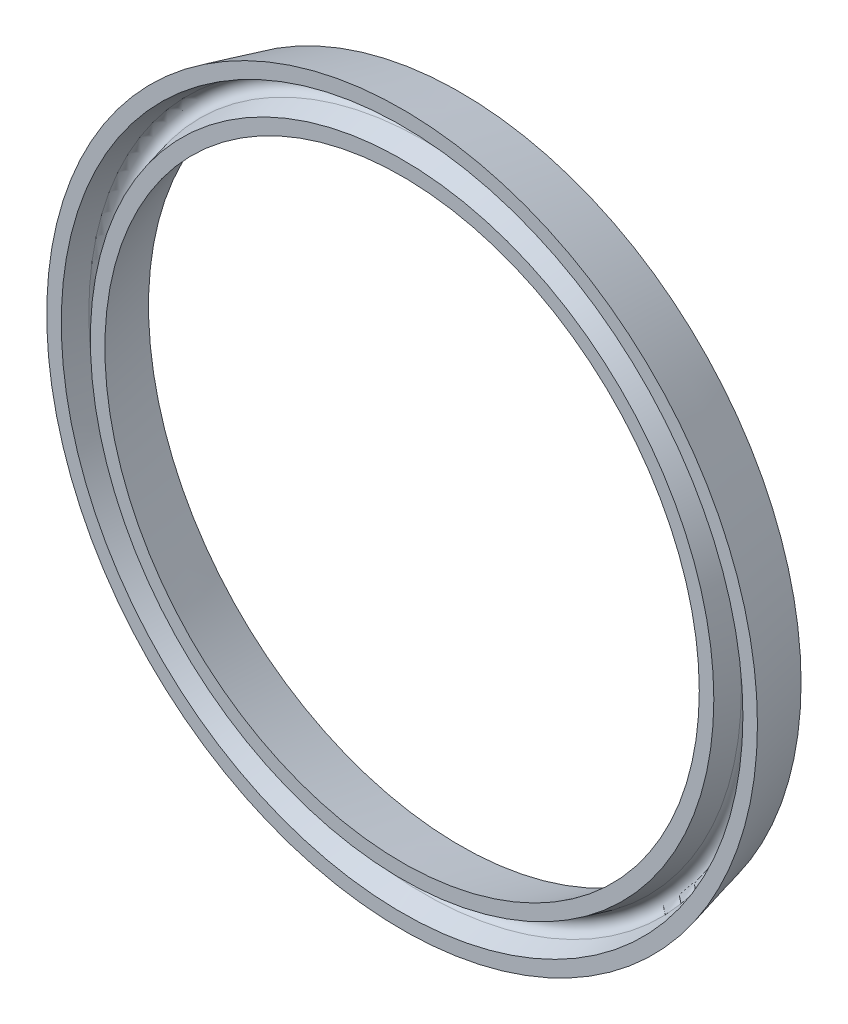
SolidWorks part; units mm, degrees
ref_plane "Front Plane" through (0, 0, 0) normal (0, 0, 1) x (1, 0, 0)
ref_plane "Top Plane" through (0, 0, 0) normal (0, 1, 0) x (1, 0, 0)
ref_plane "Right Plane" through (0, 0, 0) normal (1, 0, 0) x (0, 0, -1)
sketch "Sketch3" plane through (0, 0, 0) normal (0, 1, 0) x (1, 0, 0)
  line L0 (-3, 6) -> (3, 6)
  line L1 (3, 6) -> (6, -6)
  line L4 (-3, 6) -> (-6, -6)
  line L5 (-6, -6) -> (-3, -6)
  line L6 (-3, -6) -> (-1.8638, -1.4552)
  line L8 (1.8638, -1.4552) -> (3, -6)
  line L9 (3, -6) -> (6, -6)
  line L10 (0, 6) -> (0, 0) construction
  line L12 (6, -6) -> (-67.31, -6) construction
  line L13 (-67.31, -6) -> (-67.31, 12.8863) construction
  arc A2 (-1.8638, -1.4552) -> (1.8638, -1.4552) centre (0, -1.9212) cw
  point P4 (0, 6)
  dimension "D6" = 6
  dimension "D8" = 73.31
  dimension "D7" = 12
  dimension "D1" = 3
  dimension "D2" = 3
  dimension "D3" = 6
  dimension "D4" = 12
  dimension "D5" = 12
revolve "Revolve1" add sketch "Sketch3" angle 360 about L13
